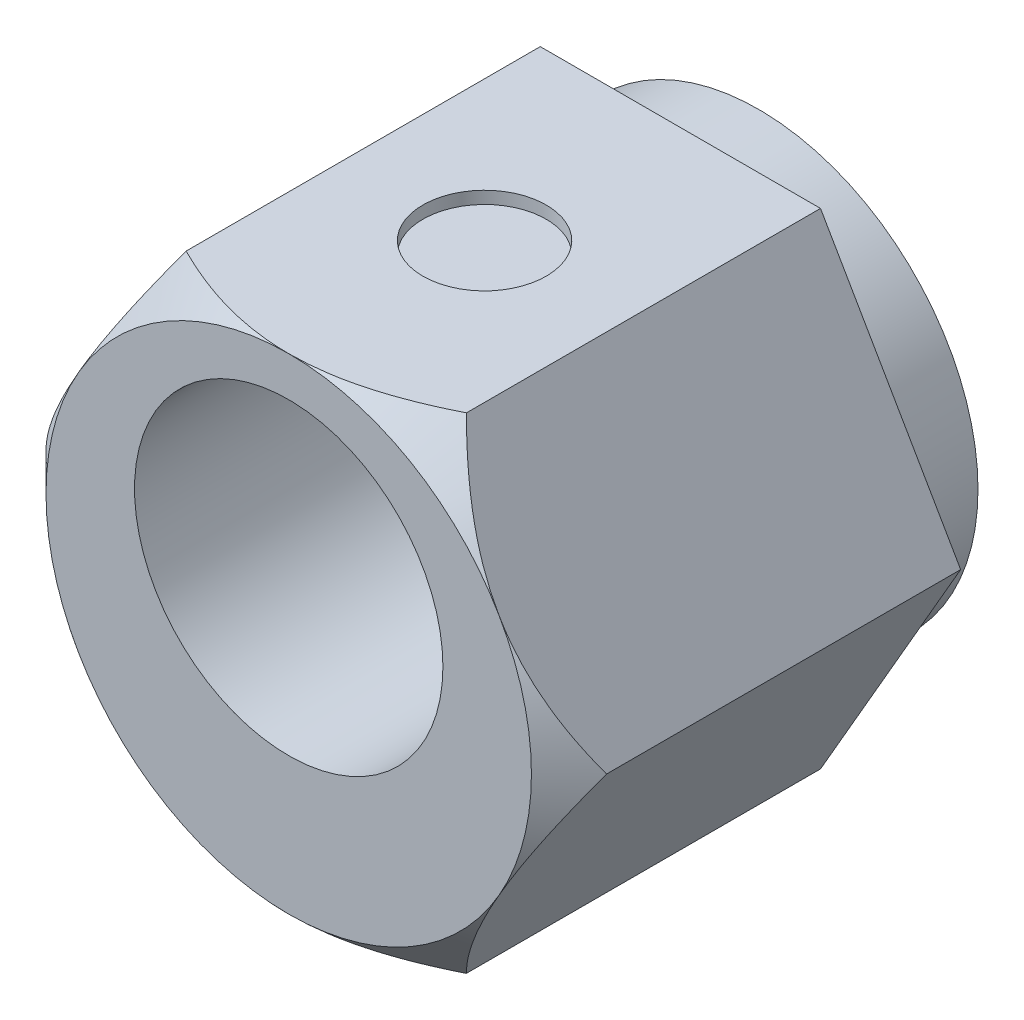
SolidWorks part; units mm, degrees
material "1.5714 (16NiCr4)"
ref_plane "Plan de face" through (0, 0, 0) normal (0, 0, 1) x (1, 0, 0)
ref_plane "Plan de dessus" through (0, 0, 0) normal (0, 1, 0) x (1, 0, 0)
ref_plane "Plan de droite" through (0, 0, 0) normal (1, 0, 0) x (0, 0, -1)
sketch "Esquisse1" plane through (0, 0, 0) normal (0, 0, 1) x (1, 0, 0)
  circle A0 centre (0, 0) radius 3.555
  dimension "D1" = 7.11
extrude "Boss.-Extru.1" add sketch "Esquisse1" against normal blind 1.27
sketch "Esquisse2" plane through (0, 0, 0) normal (0, 0, 1) x (1, 0, 0)
  line L1 (4.5437, 0) -> (2.2719, 3.935)
  line L2 (2.2719, 3.935) -> (-2.2719, 3.935)
  line L3 (-2.2719, 3.935) -> (-4.5437, 0)
  line L4 (-4.5437, 0) -> (-2.2719, -3.935)
  line L5 (-2.2719, -3.935) -> (2.2719, -3.935)
  line L6 (2.2719, -3.935) -> (4.5437, 0)
  circle A0 centre (0, 0) radius 3.935 construction
  dimension "D1" = 7.87
extrude "Boss.-Extru.2" add sketch "Esquisse2" along normal blind 6.35
sketch "Esquisse3" plane through (0, 0, 6.35) normal (0, 0, 1) x (1, 0, 0)
  circle A0 centre (0, 0.79) radius 2.5
  dimension "D1" = 5
  dimension "D2" = 0.79
extrude "Enlèv. mat.-Extru.1" cut sketch "Esquisse3" against normal through all
sketch "Esquisse4" plane through (0, 3.935, 0) normal (0, 1, 0) x (1, 0, 0)
  line L0 (-2.2719, 0) -> (2.2719, -6.35) construction
  circle A0 centre (0, -3.175) radius 1
  dimension "D1" = 2
extrude "Enlèv. mat.-Extru.2" cut sketch "Esquisse4" against normal blind 0.2
ref_plane "Plan1" through (0, 0, 0) normal (-0.5, 0.866, 0) x (-0.866, -0.5, 0)
sketch "Esquisse5" plane through (0, 0, 0) normal (-0.5, 0.866, 0) x (-0.866, -0.5, 0)
  line L0 (-3.935, 6.35) -> (-10.285, 0)
  line L1 (-10.285, 0) -> (-10.285, 6.35)
  line L2 (-10.285, 6.35) -> (-3.935, 6.35)
  line L3 (-3.935, 6.35) -> (-3.935, 0) construction
  line L4 (-3.935, 0) -> (0, 0) construction
  line L5 (0, 0) -> (0, 6.35) construction
  dimension "D1" = 45
revolve "Enlèvement de matière-Révolution1" cut sketch "Esquisse5" angle 360 about L5
